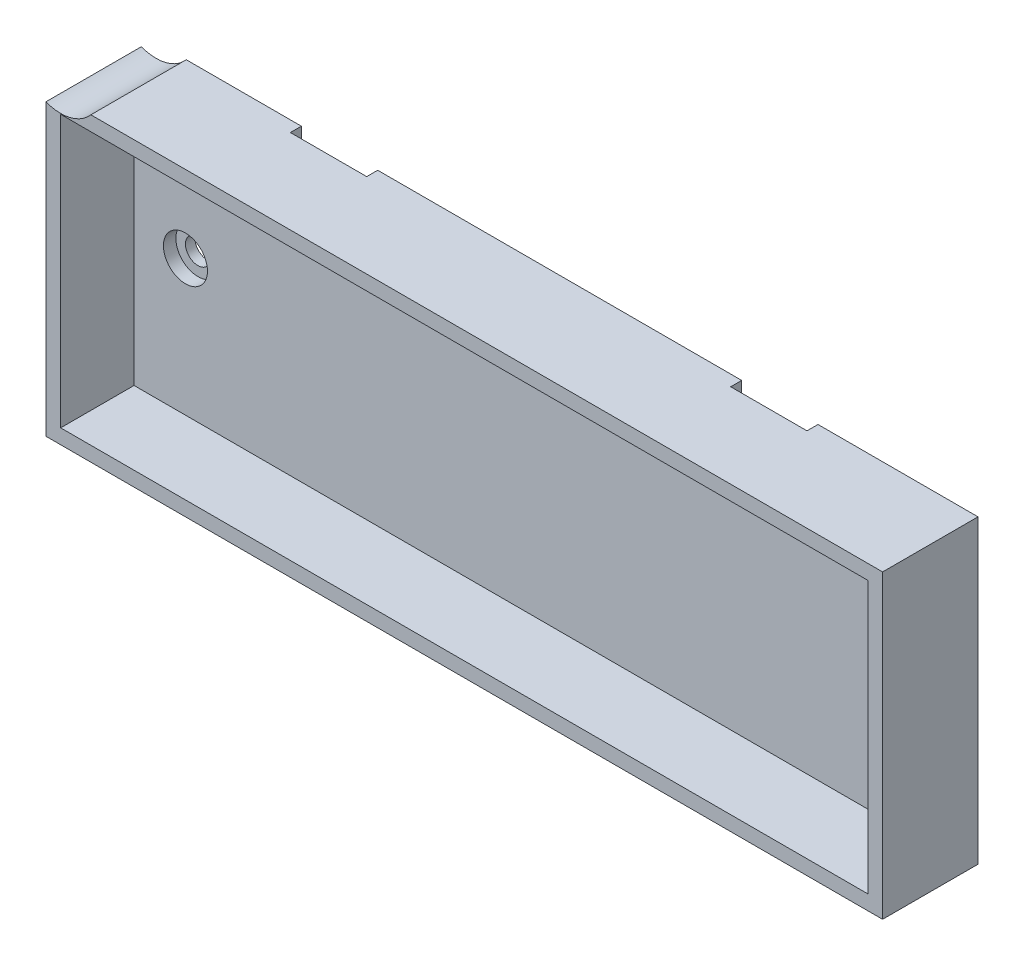
SolidWorks part; units mm, degrees
other "Battery Tray Left"
ref_plane "Front Plane" through (0, 0, 0) normal (0, 0, 1) x (1, 0, 0)
ref_plane "Top Plane" through (0, 0, 0) normal (0, 1, 0) x (1, 0, 0)
ref_plane "Right Plane" through (0, 0, 0) normal (1, 0, 0) x (0, 0, -1)
sketch3d "Main Profile Sketch datum points"
  point P0 (0, 0, 61.5)
  point P1 (10, 0, 61.5)
  point P2 (0, 10, 61.5)
ref_plane "Main Profile Sketch plane" through (0, 0, 61.5) normal (0, 0, 1) x (1, 0, 0)
sketch "Main Profile Sketch" plane through (0, 0, 61.5) normal (0, 0, 1) x (1, 0, 0)
  line L0 (-265.8878, 47) -> (-158, 47)
  line L1 (-158, 47) -> (-158, 6)
  line L2 (-272, 6) -> (-158, 6)
  line L3 (-272, 45.484) -> (-272, 6)
  line L4 (-270, 45) -> (-270, 8)
  line L5 (-270, 8) -> (-160, 8)
  line L6 (-160, 45) -> (-160, 8)
  line L7 (-270, 45) -> (-160, 45)
  arc A0 (-272, 45.484) -> (-265.8878, 47) centre (-270, 50.5) ccw
extrude "Main Extrusion" add sketch "Main Profile Sketch" against normal blind 10 separate body
sketch3d "Detail Profile 2 Sketch datum points"
  point P0 (0, 0, 51.5)
  point P1 (10, 0, 51.5)
  point P2 (0, 10, 51.5)
ref_plane "Detail Profile 2 Sketch plane" through (0, 0, 51.5) normal (0, 0, 1) x (1, 0, 0)
sketch "Detail Profile 2 Sketch" plane through (0, 0, 51.5) normal (0, 0, 1) x (1, 0, 0)
  line L0 (-265.8878, 47) -> (-158, 47)
  line L1 (-158, 47) -> (-158, 6)
  line L2 (-272, 6) -> (-158, 6)
  line L3 (-272, 45.484) -> (-272, 6)
  arc A0 (-272, 45.484) -> (-265.8878, 47) centre (-270, 50.5) ccw
  circle A1 centre (-263, 26.5) radius 3
  circle A2 centre (-167, 26.5) radius 3
extrude "Detail Extrusion 2" add sketch "Detail Profile 2 Sketch" against normal blind 1.5
sketch3d "Detail Profile 3 Sketch datum points"
  point P0 (0, 0, 50)
  point P1 (10, 0, 50)
  point P2 (0, 10, 50)
ref_plane "Detail Profile 3 Sketch plane" through (0, 0, 50) normal (0, 0, 1) x (1, 0, 0)
sketch "Detail Profile 3 Sketch" plane through (0, 0, 50) normal (0, 0, 1) x (1, 0, 0)
  line L0 (-265.8878, 47) -> (-250.2, 47)
  line L1 (-250.2, 47) -> (-250.2, 6)
  line L2 (-272, 6) -> (-250.2, 6)
  line L3 (-272, 45.484) -> (-272, 6)
  line L4 (-179.8, 47) -> (-158, 47)
  line L5 (-158, 47) -> (-158, 6)
  line L6 (-179.8, 6) -> (-158, 6)
  line L7 (-179.8, 47) -> (-179.8, 6)
  line L8 (-239.8, 47) -> (-190.2, 47)
  line L9 (-190.2, 47) -> (-190.2, 6)
  line L10 (-239.8, 6) -> (-190.2, 6)
  line L11 (-239.8, 47) -> (-239.8, 6)
  arc A0 (-272, 45.484) -> (-265.8878, 47) centre (-270, 50.5) ccw
  circle A1 centre (-263, 26.5) radius 3
  circle A2 centre (-167, 26.5) radius 3
extrude "Detail Extrusion 3" add sketch "Detail Profile 3 Sketch" against normal blind 0.2
sketch3d "Detail Profile 4 Sketch datum points"
  point P0 (0, 0, 49.8)
  point P1 (10, 0, 49.8)
  point P2 (0, 10, 49.8)
ref_plane "Detail Profile 4 Sketch plane" through (0, 0, 49.8) normal (0, 0, 1) x (1, 0, 0)
sketch "Detail Profile 4 Sketch" plane through (0, 0, 49.8) normal (0, 0, 1) x (1, 0, 0)
  line L0 (-265.8878, 47) -> (-250.2, 47)
  line L1 (-250.2, 47) -> (-250.2, 6)
  line L2 (-272, 6) -> (-250.2, 6)
  line L3 (-272, 45.484) -> (-272, 6)
  line L4 (-239.8, 47) -> (-190.2, 47)
  line L5 (-190.2, 47) -> (-190.2, 6)
  line L6 (-239.8, 6) -> (-190.2, 6)
  line L7 (-239.8, 47) -> (-239.8, 6)
  line L8 (-179.8, 47) -> (-158, 47)
  line L9 (-158, 47) -> (-158, 6)
  line L10 (-179.8, 6) -> (-158, 6)
  line L11 (-179.8, 47) -> (-179.8, 6)
  arc A0 (-272, 45.484) -> (-265.8878, 47) centre (-270, 50.5) ccw
  circle A1 centre (-263, 26.5) radius 1.7
  circle A2 centre (-167, 26.5) radius 1.7
extrude "Detail Extrusion 4" add sketch "Detail Profile 4 Sketch" against normal blind 1.3
